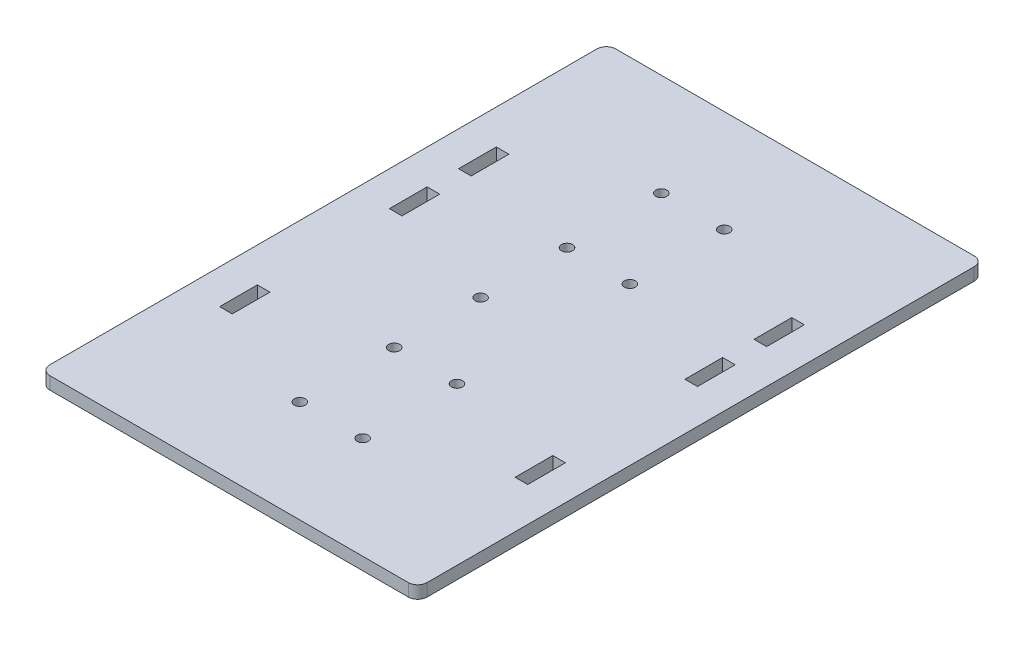
SolidWorks part; units mm, degrees
ref_plane "Front Plane" through (0, 0, 0) normal (0, 0, 1) x (1, 0, 0)
ref_plane "Top Plane" through (0, 0, 0) normal (0, 1, 0) x (1, 0, 0)
ref_plane "Right Plane" through (0, 0, 0) normal (1, 0, 0) x (0, 0, -1)
sketch "Sketch1" plane through (0, 0, 0) normal (0, 1, 0) x (1, 0, 0)
  line L0 (-55, 0) -> (55, 0) construction
  line L1 (-60, 90) -> (60, 90)
  line L2 (-60, 90) -> (-60, -90)
  line L3 (-60, -90) -> (60, -90)
  line L4 (60, 90) -> (60, -90)
  line L5 (-60, 90) -> (60, -90) construction
  line L6 (-60, -90) -> (60, 90) construction
  line L7 (-45, 10) -> (-49, 10)
  line L8 (-45, 44) -> (-49, 44)
  line L9 (-45, 44) -> (-45, 32)
  line L10 (-45, 32) -> (-49, 32)
  line L11 (-49, 44) -> (-49, 32)
  line L12 (-45, 22) -> (-45, 10)
  line L13 (-49, 22) -> (-49, 10)
  line L14 (-45, 22) -> (-49, 22)
  line L15 (-45, -44) -> (-49, -44)
  line L16 (-45, -32) -> (-45, -44)
  line L17 (-49, -32) -> (-49, -44)
  line L18 (-45, -32) -> (-49, -32)
  line L19 (0, -55) -> (0, 55) construction
  line L20 (45, -44) -> (49, -44)
  line L21 (49, -32) -> (49, -44)
  line L22 (45, -32) -> (45, -44)
  line L23 (45, -32) -> (49, -32)
  line L24 (45, 10) -> (49, 10)
  line L25 (45, 22) -> (45, 10)
  line L26 (49, 22) -> (49, 10)
  line L27 (45, 22) -> (49, 22)
  line L28 (45, 44) -> (49, 44)
  line L29 (45, 32) -> (49, 32)
  line L30 (49, 44) -> (49, 32)
  line L31 (45, 44) -> (45, 32)
  circle A11 centre (-10, 57.5) radius 1.75
  circle A12 centre (10, 57.5) radius 1.75
  circle A13 centre (10, 27.5) radius 1.75
  circle A14 centre (-10, 27.5) radius 1.75
  circle A15 centre (10, -27.5) radius 1.75
  circle A16 centre (-10, -27.5) radius 1.75
  circle A17 centre (10, -57.5) radius 1.75
  circle A18 centre (-10, -57.5) radius 1.75
  circle A19 centre (-10, 0) radius 1.75
  point P0 (0, 0)
  point P30 (-45, 38)
  point P31 (-47, 22)
  dimension "D3" = 3.5
  dimension "D11" = 3.5
  dimension "D1" = 120
  dimension "D2" = 180
  dimension "D4" = 32.5
  dimension "D5" = 50
  dimension "D8" = 20
  dimension "D9" = 30
  dimension "D10" = 36.0555
  dimension "D12" = 10
  dimension "D21" = 46
  dimension "D22" = 15
  dimension "D23" = 4
  dimension "D24" = 12
  dimension "D26" = 10
  dimension "D27" = 2
  dimension "D28" = 42
  dimension "D25" = 2
  dimension "D6" = 2
  dimension "D7" = 2
extrude "Boss-Extrude1" add sketch "Sketch1" along normal blind 4
fillet "Fillet1" radius 3 4 edges at (-60, 2, -90) (60, 2, -90) (60, 2, 90) (-60, 2, 90)
